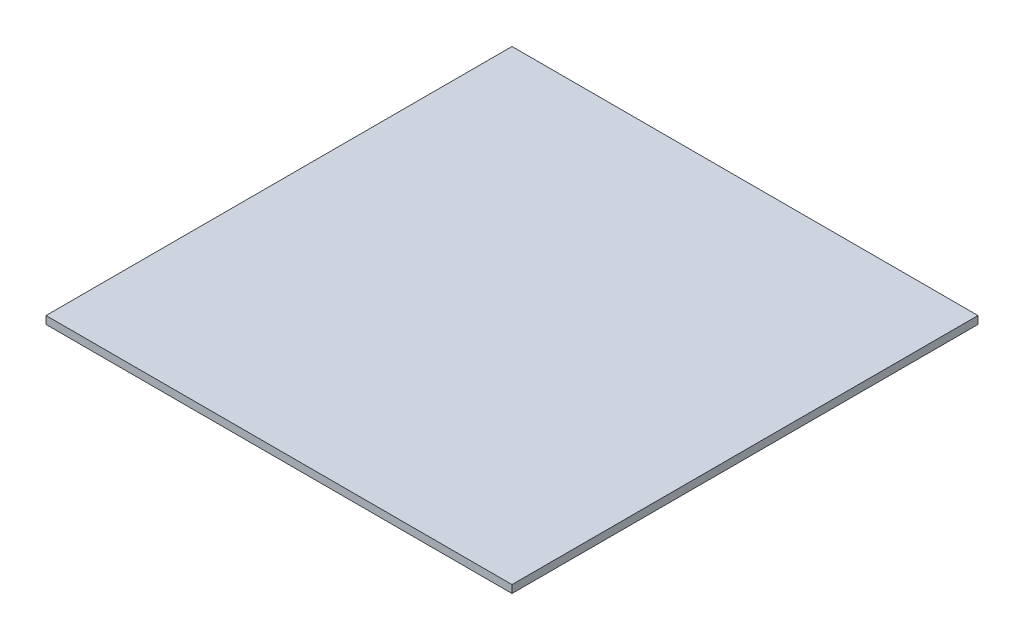
SolidWorks part; units mm, degrees
material "Glass"
ref_plane "Front Plane" through (0, 0, 0) normal (0, 0, 1) x (1, 0, 0)
ref_plane "Top Plane" through (0, 0, 0) normal (0, 1, 0) x (1, 0, 0)
ref_plane "Right Plane" through (0, 0, 0) normal (1, 0, 0) x (0, 0, -1)
sketch "Sketch1" plane through (0, 0, 0) normal (0, 1, 0) x (1, 0, 0)
  line L1 (0, 0) -> (152.4, 0)
  line L2 (0, 0) -> (0, 152.4)
  line L3 (0, 152.4) -> (152.4, 152.4)
  line L4 (152.4, 0) -> (152.4, 152.4)
  dimension "D1" = 152.4
  dimension "D2" = 152.4
extrude "Boss-Extrude1" add sketch "Sketch1" along normal blind 2.54
